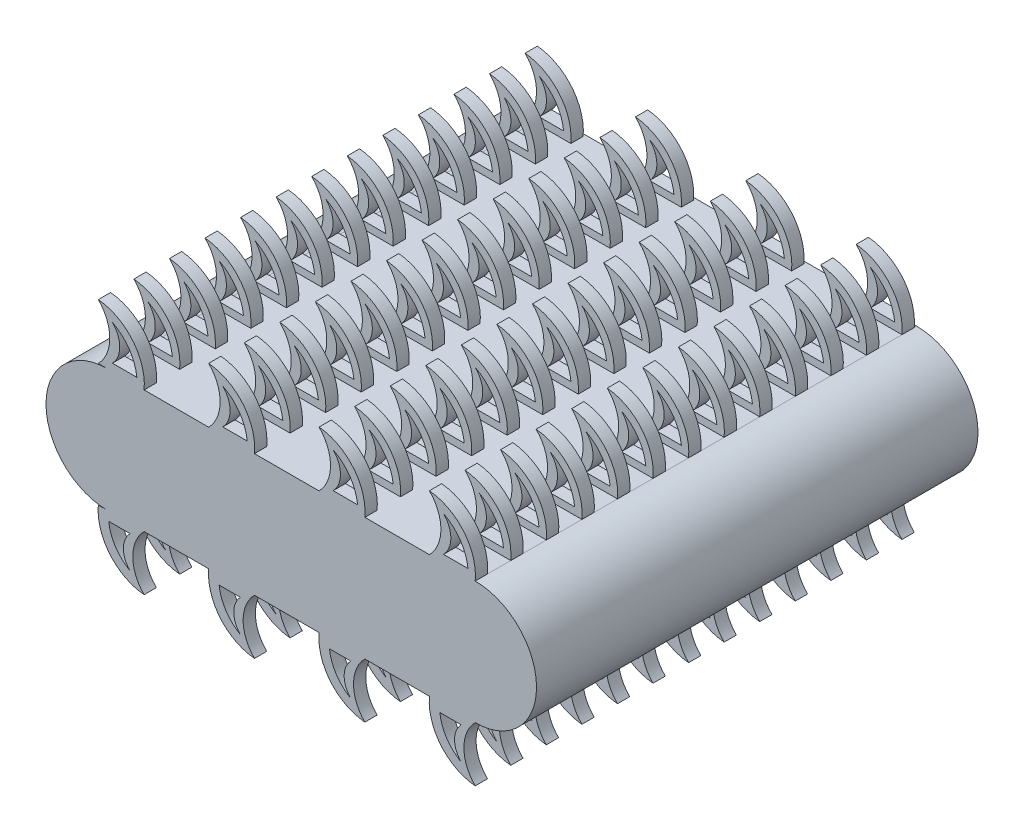
SolidWorks part; units mm, degrees
ref_plane "Front Plane" through (0, 0, 0) normal (0, 0, 1) x (1, 0, 0)
ref_plane "Top Plane" through (0, 0, 0) normal (0, 1, 0) x (1, 0, 0)
ref_plane "Right Plane" through (0, 0, 0) normal (1, 0, 0) x (0, 0, -1)
sketch "Sketch1" plane through (0, 0, 0) normal (0, 0, 1) x (1, 0, 0)
  line L0 (0, 0) -> (300, 0) construction
  line L1 (0, 50) -> (300, 50)
  line L2 (0, -50) -> (300, -50)
  arc A0 (0, 50) -> (0, -50) centre (0, 0) ccw
  arc A1 (300, -50) -> (300, 50) centre (300, 0) ccw
  point P3 (150, 0)
  dimension "D1" = 300
  dimension "D2" = 100
extrude "Boss-Extrude1" add sketch "Sketch1" along normal blind 360
sketch "Sketch2" plane through (0, 0, 360) normal (0, 0, 1) x (1, 0, 0)
  line L0 (300, 50) -> (262.6504, 50)
  line L1 (300, 50) -> (0, 50) construction
  line L3 (210, 50) -> (172.6504, 50)
  line L4 (120, 50) -> (82.6504, 50)
  line L5 (30, 50) -> (-7.3496, 50)
  arc A0 (262.6504, 95.1169) -> (300, 50) centre (258.7668, 53.8837) cw
  arc A1 (262.6504, 95.1169) -> (262.6504, 50) centre (240.092, 72.5584) cw
  arc A2 (172.6504, 95.1169) -> (172.6504, 50) centre (150.092, 72.5584) cw
  arc A3 (172.6504, 95.1169) -> (210, 50) centre (168.7668, 53.8837) cw
  arc A4 (82.6504, 95.1169) -> (82.6504, 50) centre (60.092, 72.5584) cw
  arc A5 (82.6504, 95.1169) -> (120, 50) centre (78.7668, 53.8837) cw
  arc A6 (-7.3496, 95.1169) -> (-7.3496, 50) centre (-29.908, 72.5584) cw
  arc A7 (-7.3496, 95.1169) -> (30, 50) centre (-11.2332, 53.8837) cw
  dimension "D1" = 4
extrude "Boss-Extrude2" add sketch "Sketch2" against normal blind 10
pattern_linear "LPattern1" count 13 spacing 29 along (0, 0, -1) of "Boss-Extrude2"
sketch "Sketch3" plane through (0, 0, 360) normal (0, 0, 1) x (1, 0, 0)
  line L0 (274.128, 55.9285) -> (294.1075, 55.9285)
  line L1 (184.128, 55.9285) -> (204.1075, 55.9285)
  line L2 (94.128, 55.9285) -> (114.1075, 55.9285)
  line L3 (4.128, 55.9285) -> (24.1075, 55.9285)
  arc A0 (274.128, 55.9285) -> (274.128, 84.835) centre (259.6748, 70.3817) ccw
  arc A1 (274.128, 84.835) -> (294.1075, 55.9285) centre (257.4213, 51.9298) cw
  arc A2 (184.128, 84.835) -> (204.1075, 55.9285) centre (167.4213, 51.9298) cw
  arc A3 (184.128, 55.9285) -> (184.128, 84.835) centre (169.6748, 70.3817) ccw
  arc A4 (94.128, 84.835) -> (114.1075, 55.9285) centre (77.4213, 51.9298) cw
  arc A5 (94.128, 55.9285) -> (94.128, 84.835) centre (79.6748, 70.3817) ccw
  arc A6 (4.128, 84.835) -> (24.1075, 55.9285) centre (-12.5787, 51.9298) cw
  arc A7 (4.128, 55.9285) -> (4.128, 84.835) centre (-10.3252, 70.3817) ccw
  dimension "D1" = 4
extrude "Cut-Extrude1" cut sketch "Sketch3" against normal blind 360
sketch "Sketch4" plane through (0, 0, 360) normal (0, 0, 1) x (1, 0, 0)
  line L0 (262.6504, -50) -> (300, -50)
  line L1 (0, -50) -> (300, -50) construction
  line L3 (271.1523, -57.2237) -> (288.5813, -57.2237)
  line L4 (172.6504, -50) -> (210, -50)
  line L5 (82.6504, -50) -> (120, -50)
  line L6 (-7.3496, -50) -> (30, -50)
  line L7 (181.1523, -57.2237) -> (198.5813, -57.2237)
  line L8 (91.1523, -57.2237) -> (108.5813, -57.2237)
  line L9 (1.1523, -57.2237) -> (18.5813, -57.2237)
  arc A0 (262.6504, -50) -> (300, -94.6321) centre (303.6413, -53.6413) ccw
  arc A1 (300, -50) -> (300, -94.6321) centre (322.3161, -72.3161) ccw
  arc A2 (271.1523, -57.2237) -> (288.5813, -83.5796) centre (305.5952, -53.3877) ccw
  arc A3 (288.5813, -83.5796) -> (288.5813, -57.2237) centre (301.7592, -70.4017) cw
  arc A4 (210, -50) -> (210, -94.6321) centre (232.3161, -72.3161) ccw
  arc A5 (172.6504, -50) -> (210, -94.6321) centre (213.6413, -53.6413) ccw
  arc A6 (120, -50) -> (120, -94.6321) centre (142.3161, -72.3161) ccw
  arc A7 (82.6504, -50) -> (120, -94.6321) centre (123.6413, -53.6413) ccw
  arc A8 (30, -50) -> (30, -94.6321) centre (52.3161, -72.3161) ccw
  arc A9 (-7.3496, -50) -> (30, -94.6321) centre (33.6413, -53.6413) ccw
  arc A10 (198.5813, -83.5796) -> (198.5813, -57.2237) centre (211.7592, -70.4017) cw
  arc A11 (181.1523, -57.2237) -> (198.5813, -83.5796) centre (215.5952, -53.3877) ccw
  arc A12 (108.5813, -83.5796) -> (108.5813, -57.2237) centre (121.7592, -70.4017) cw
  arc A13 (91.1523, -57.2237) -> (108.5813, -83.5796) centre (125.5952, -53.3877) ccw
  arc A14 (18.5813, -83.5796) -> (18.5813, -57.2237) centre (31.7592, -70.4017) cw
  arc A15 (1.1523, -57.2237) -> (18.5813, -83.5796) centre (35.5952, -53.3877) ccw
  dimension "D1" = 4
  dimension "D2" = 4
extrude "Boss-Extrude3" add sketch "Sketch4" against normal blind 10
pattern_linear "LPattern2" count 13 spacing 29 along (0, 0, -1) of "Boss-Extrude3"
